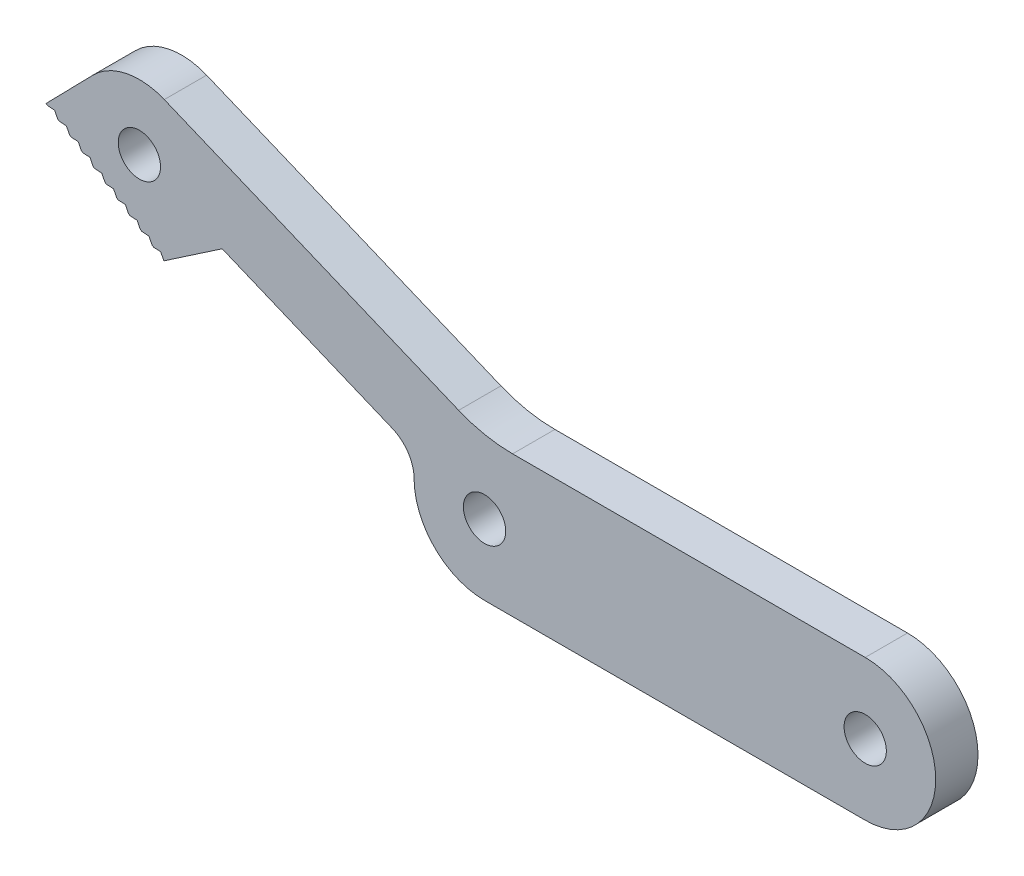
SolidWorks part; units mm, degrees
material "Cast Stainless Steel"
ref_plane "Front Plane" through (0, 0, 0) normal (0, 0, 1) x (1, 0, 0)
ref_plane "Top Plane" through (0, 0, 0) normal (0, 1, 0) x (1, 0, 0)
ref_plane "Right Plane" through (0, 0, 0) normal (1, 0, 0) x (0, 0, -1)
sketch "Sketch1" plane through (0, 0, 0) normal (0, 0, 1) x (1, 0, 0)
  line L0 (-13.5, 0) -> (13.5, 0) construction
  line L1 (-11.5109, 5) -> (13.5, 5)
  line L2 (-13.5, -5) -> (13.5, -5)
  line L3 (-37.9828, 10.1411) -> (-13.5, 0) construction
  line L4 (-15.3377, 5.7612) -> (-36.215, 14.4089)
  line L5 (-32.1098, 7.2965) -> (-20.0433, 2.2984)
  line L6 (-18.2516, 1.5562) -> (-15.4134, 0.3806) construction
  line L7 (-37.9828, 10.1411) -> (-36.215, 14.4089) construction
  line L8 (-36.215, 14.4089) -> (-37.9828, 10.1411) construction
  line L9 (13.5, 5) -> (13.5, -5) construction
  line L10 (-32.1098, 7.2965) -> (-36.2454, 4.4863)
  line L11 (-41.2869, 13.3694) -> (-44.6065, 9.972)
  line L12 (-36.2454, 4.4863) -> (-44.6065, 9.972)
  arc A0 (-18.5, -0.0076) -> (-13.5, -5) centre (-13.5, 0) ccw
  arc A1 (13.5, -5) -> (13.5, 5) centre (13.5, 0) ccw
  circle A2 centre (-13.5, 0) radius 1.5
  circle A3 centre (13.5, 0) radius 1.5
  circle A4 centre (-37.9828, 10.1411) radius 1.5
  arc A5 (-36.215, 14.4089) -> (-41.2869, 13.3694) centre (-37.9828, 10.1411) ccw
  arc A6 (-33.715, 8.3733) -> (-36.215, 14.4089) centre (-37.9828, 10.1411) ccw construction
  arc A7 (-39.8117, 5.8992) -> (-33.715, 8.3733) centre (-37.9828, 10.1411) ccw construction
  arc A8 (-41.2869, 13.3694) -> (-39.8117, 5.8992) centre (-37.9828, 10.1411) ccw construction
  arc A9 (-13.5, 5) -> (-18.1194, 1.9134) centre (-13.5, 0) ccw construction
  arc A10 (-18.1194, 1.9134) -> (-18.2516, 1.5562) centre (-13.5, 0) ccw construction
  arc A11 (-11.5109, 5) -> (-15.3377, 5.7612) centre (-11.5109, 15) cw
  arc A12 (-20.0433, 2.2984) -> (-18.5, -0.0076) centre (-21, -0.0113) cw
  point P2 (0, 0)
  point P20 (-32.1098, 7.2965)
  dimension "D3" = 3
  dimension "D4" = 3
  dimension "D13" = 10
  dimension "D14" = 2.5
  dimension "D1" = 10
  dimension "D2" = 27
  dimension "D5" = 5
  dimension "D6" = 157.5
  dimension "D7" = 15
  dimension "D8" = 26.5
  dimension "D9" = 5
  dimension "D10" = 10
  dimension "D11" = 13.5
  dimension "D12" = 5
  dimension "D15" = 4.75
extrude "Boss-Extrude1" add sketch "Sketch1" along normal blind 3
sketch "Sketch3" plane through (0, 0, 3) normal (0, 0, 1) x (1, 0, 0)
  line L0 (-36.0215, 4.6384) -> (-36.4703, 4.9329)
  line L1 (-36.2454, 4.4863) -> (-32.1098, 7.2965) construction
  line L2 (-41.2869, 13.3694) -> (-44.6065, 9.972) construction
  line L3 (-44.6065, 9.972) -> (-36.2454, 4.4863) construction
  line L4 (-44.6065, 9.972) -> (-36.2454, 4.4863)
  line L5 (-36.2454, 4.4863) -> (-36.4703, 4.9329)
  line L6 (-36.4703, 4.9329) -> (-36.9695, 4.9614)
  line L37 (-36.2031, 4.4022) -> (-36.2454, 4.4863)
  line L45 (-36.4703, 4.9329) -> (-44.4284, 10.1542) construction
  dimension "D1" = 0.25
  dimension "D2" = 30
  dimension "D3" = 120
extrude "Cut-Extrude1" cut sketch "Sketch3" against normal blind 23
pattern_linear "LPattern1" count 2 spacing 10 along (-0.8361, 0.5486, 0) count 10 spacing 1 along (0.8361, -0.5486, 0) of "Cut-Extrude1"
